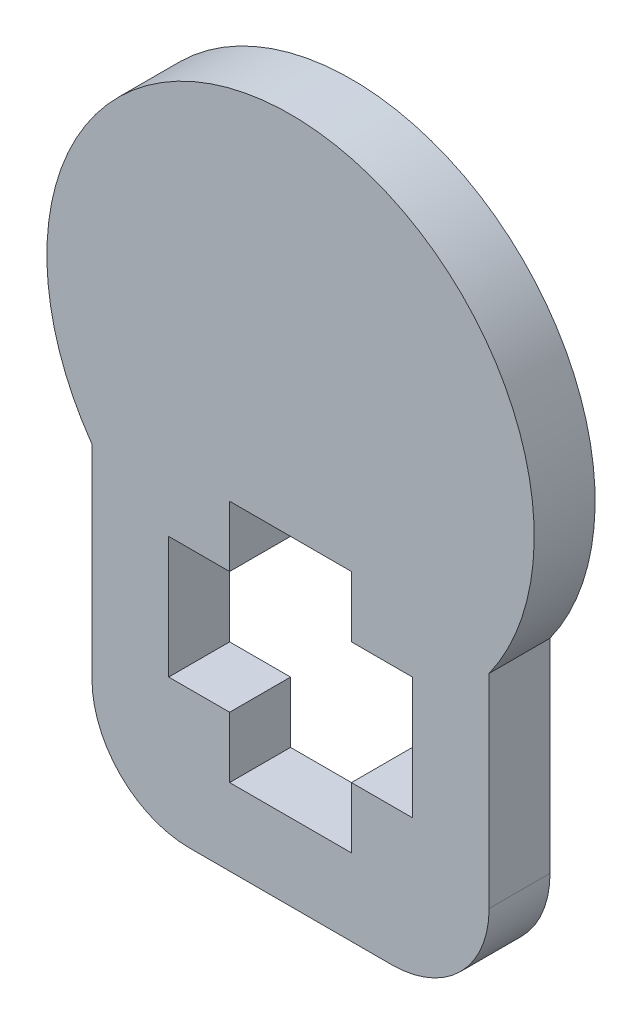
SolidWorks part; units mm, degrees
ref_plane "Front Plane" through (0, 0, 0) normal (0, 0, 1) x (1, 0, 0)
ref_plane "Top Plane" through (0, 0, 0) normal (0, 1, 0) x (1, 0, 0)
ref_plane "Right Plane" through (0, 0, 0) normal (1, 0, 0) x (0, 0, -1)
sketch "Sketch1" plane through (0, 0, 0) normal (0, 0, 1) x (1, 0, 0)
  line L0 (0, 0) -> (0, 3.175) construction
  line L1 (0, 0) -> (-3.175, 0) construction
  line L2 (-3.175, -1.5875) -> (-3.175, 1.5875)
  line L3 (-3.175, 1.5875) -> (-1.5875, 1.5875)
  line L4 (-1.5875, 1.5875) -> (-1.5875, 3.175)
  line L5 (-1.5875, 3.175) -> (1.5875, 3.175)
  line L6 (-1.5875, -3.175) -> (1.5875, -3.175)
  line L7 (-1.5875, -1.5875) -> (-1.5875, -3.175)
  line L8 (-3.175, -1.5875) -> (-1.5875, -1.5875)
  line L9 (3.175, -1.5875) -> (1.5875, -1.5875)
  line L10 (1.5875, -1.5875) -> (1.5875, -3.175)
  line L11 (1.5875, 1.5875) -> (1.5875, 3.175)
  line L12 (3.175, 1.5875) -> (1.5875, 1.5875)
  line L13 (3.175, -1.5875) -> (3.175, 1.5875)
  line L14 (0, 6.35) -> (0, 0) construction
  line L15 (-5.175, 2.6701) -> (-5.175, -5.175)
  line L16 (-5.175, -5.175) -> (5.175, -5.175)
  line L17 (5.175, -5.175) -> (5.175, 2.6701)
  line L18 (0, 0) -> (0, -5.175) construction
  arc A0 (5.175, 2.6701) -> (-5.175, 2.6701) centre (0, 6.35) ccw
  point P15 (0, -3.175)
  dimension "D1" = 12.7
  dimension "D2" = 6.35
  dimension "D3" = 1.5875
  dimension "D4" = 1.5875
  dimension "D5" = 1.5875
  dimension "D6" = 2
  dimension "D7" = 6.35
  dimension "D8" = 2
extrude "Boss-Extrude1" add sketch "Sketch1" along normal blind 1.5875
fillet "Fillet1" radius 2.54 2 edges at (5.175, -5.175, 0.7937) (-5.175, -5.175, 0.7937)
